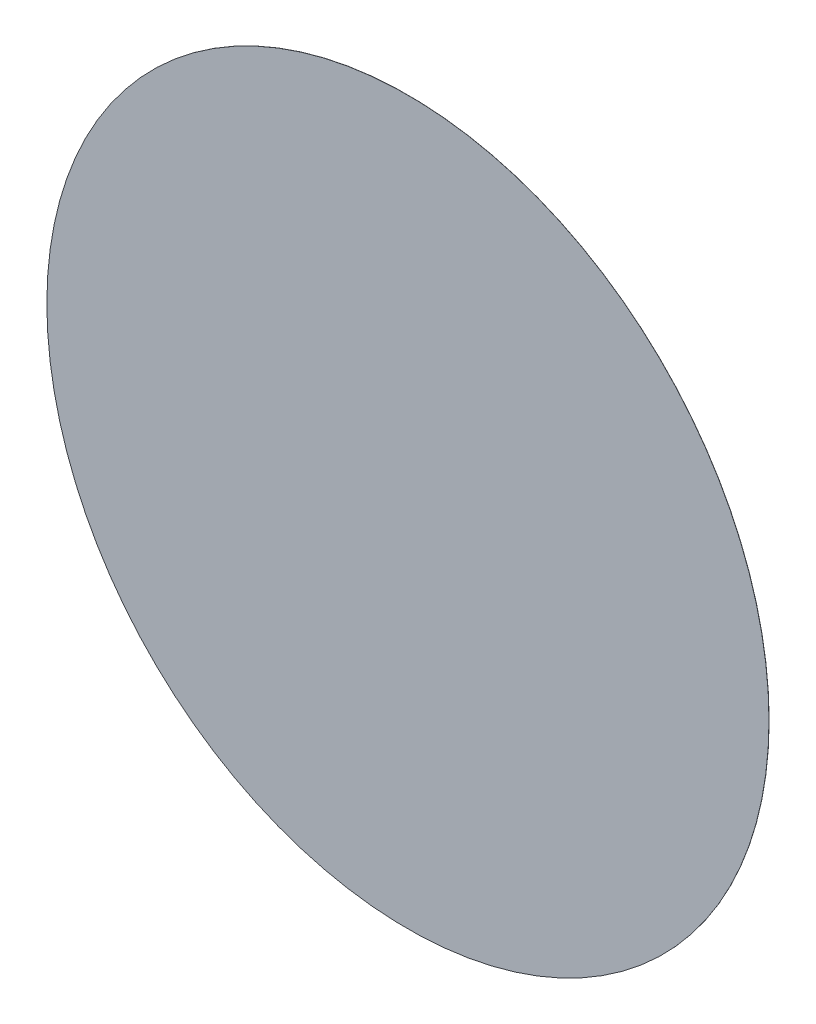
SolidWorks part; units mm, degrees
ref_plane "前视基准面" through (0, 0, 0) normal (0, 0, 1) x (1, 0, 0)
ref_plane "上视基准面" through (0, 0, 0) normal (0, 1, 0) x (1, 0, 0)
ref_plane "右视基准面" through (0, 0, 0) normal (1, 0, 0) x (0, 0, -1)
sketch "草图1" plane through (0, 0, 0) normal (0, 0, 1) x (1, 0, 0)
  circle A0 centre (-0.0979, 0.1036) radius 250.1588
extrude "凸台-拉伸1" add sketch "草图1" along normal blind 0.1
